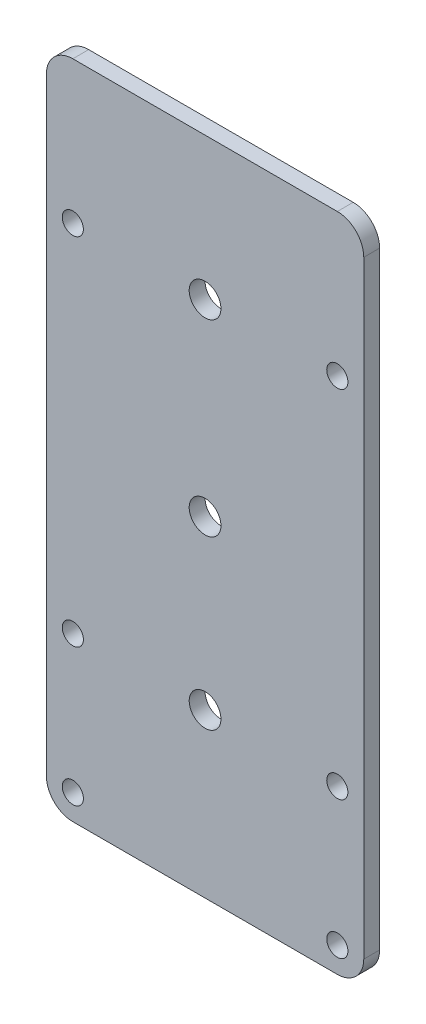
SolidWorks part; units mm, degrees
ref_plane "Спереди" through (0, 0, 0) normal (0, 0, 1) x (1, 0, 0)
ref_plane "Сверху" through (0, 0, 0) normal (0, 1, 0) x (1, 0, 0)
ref_plane "Справа" through (0, 0, 0) normal (1, 0, 0) x (0, 0, -1)
sketch "Эскиз1" plane through (0, 0, 0) normal (0, 0, 1) x (1, 0, 0)
  line L5 (30, 62.4479) -> (-30, 62.4479)
  line L6 (30, 62.4479) -> (30, -62.4479)
  line L7 (30, -62.4479) -> (-30, -62.4479)
  line L8 (-30, 62.4479) -> (-30, -62.4479)
  line L9 (30, 62.4479) -> (-30, -62.4479) construction
  line L10 (30, -62.4479) -> (-30, 62.4479) construction
  line L11 (27.6941, -57.6479) -> (-27.6941, -57.6479) construction
  line L13 (-25, -57.6479) -> (-25, 56.4449) construction
  line L14 (0, -62.4479) -> (0, 62.4479) construction
  line L15 (0, -57.6479) -> (0, -31.6479) construction
  line L16 (0, -31.6479) -> (0, 35.5321) construction
  line L17 (0, -31.6479) -> (-25, -31.6479) construction
  line L18 (0, 35.5321) -> (-25, 35.5321) construction
  circle A0 centre (-25, -57.6479) radius 2
  circle A1 centre (-25, -31.6479) radius 2
  circle A2 centre (-25, 35.5321) radius 2
  circle A3 centre (0, -31.6479) radius 3
  circle A4 centre (0, 35.5321) radius 3
  circle A5 centre (25, 35.5321) radius 2
  circle A6 centre (25, -31.6479) radius 2
  circle A7 centre (25, -57.6479) radius 2
  point P0 (0, 0)
  dimension "D1" = 4.8
  dimension "D2" = 5
  dimension "D4" = 67.18
  dimension "D5" = 60
  dimension "D3" = 26
  dimension "D6" = 25
  dimension "D7" = 25
extrude "Бобышка-Вытянуть1" add sketch "Эскиз1" along normal blind 3
fillet "Скругление2" radius 5 1 edges at (-30, 62.4479, 1.5)
fillet "Скругление3" radius 5 1 edges at (30, 62.4479, 1.5)
fillet "Скругление4" radius 5 1 edges at (30, -62.4479, 1.5)
fillet "Скругление5" radius 5 1 edges at (-30, -62.4479, 1.5)
sketch "Эскиз2" plane through (0, 0, 3) normal (0, 0, 1) x (1, 0, 0)
  circle A0 centre (0, 0) radius 3
  dimension "D1" = 6
extrude "Вырез-Вытянуть1" cut sketch "Эскиз2" against normal blind 3
